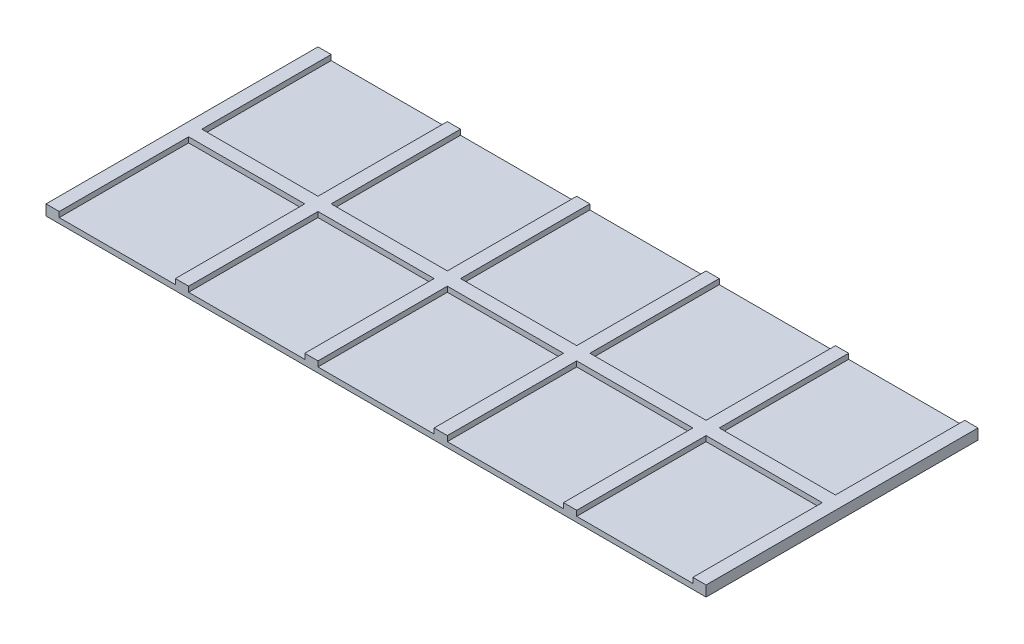
SolidWorks part; units mm, degrees
ref_plane "Front Plane" through (0, 0, 0) normal (0, 0, 1) x (1, 0, 0)
ref_plane "Top Plane" through (0, 0, 0) normal (0, 1, 0) x (1, 0, 0)
ref_plane "Right Plane" through (0, 0, 0) normal (1, 0, 0) x (0, 0, -1)
sketch "Sketch1" plane through (0, 0, 0) normal (0, 1, 0) x (1, 0, 0)
  line L1 (-122.5, 128.75) -> (122.5, 128.75)
  line L5 (122.5, 128.75) -> (367.5, 128.75)
  line L9 (367.5, 128.75) -> (612.5, 128.75)
  line L13 (-367.5, 128.75) -> (-122.5, 128.75)
  line L17 (-612.5, 128.75) -> (-367.5, 128.75)
  line L20 (612.5, 128.75) -> (625, 128.75)
  line L21 (625, 128.75) -> (625, -386.25)
  line L22 (-355, -116.25) -> (-135, -116.25)
  line L23 (-355, -141.25) -> (-135, -141.25)
  line L24 (625, 128.75) -> (600, 128.75)
  line L25 (600, 128.75) -> (600, -386.25)
  line L26 (-110, -116.25) -> (110, -116.25)
  line L27 (355, 128.75) -> (380, 128.75)
  line L28 (380, 128.75) -> (380, -386.25)
  line L30 (355, -386.25) -> (355, 128.75)
  line L31 (110, 128.75) -> (135, 128.75)
  line L32 (135, 128.75) -> (135, -386.25)
  line L34 (110, 128.75) -> (110, -386.25)
  line L35 (625, 128.75) -> (600, 128.75)
  line L36 (-110, -141.25) -> (110, -141.25)
  line L37 (600, 128.75) -> (612.5, 128.75)
  line L38 (-110, 128.75) -> (-135, 128.75)
  line L39 (-135, 128.75) -> (-135, -386.25)
  line L41 (-110, 128.75) -> (-110, -386.25)
  line L43 (-380, 128.75) -> (-380, -386.25)
  line L44 (-355, 128.75) -> (-380, 128.75)
  line L45 (-355, -386.25) -> (-355, 128.75)
  line L46 (135, -116.25) -> (355, -116.25)
  line L47 (-600, 128.75) -> (-600, -386.25)
  line L48 (-625, 128.75) -> (-625, -386.25)
  line L49 (-612.5, 128.75) -> (-625, 128.75)
  line L50 (-600, 128.75) -> (-612.5, 128.75)
  line L52 (-600, -116.25) -> (-380, -116.25)
  line L57 (-600, -386.25) -> (-612.5, -386.25)
  line L58 (-612.5, -386.25) -> (-625, -386.25)
  line L59 (-355, -386.25) -> (-380, -386.25)
  line L60 (-110, -386.25) -> (-135, -386.25)
  line L61 (600, -386.25) -> (612.5, -386.25)
  line L62 (625, -386.25) -> (600, -386.25)
  line L63 (110, -386.25) -> (135, -386.25)
  line L64 (355, -386.25) -> (380, -386.25)
  line L65 (625, -386.25) -> (600, -386.25)
  line L66 (612.5, -386.25) -> (625, -386.25)
  line L67 (-612.5, -386.25) -> (-367.5, -386.25)
  line L68 (-367.5, -386.25) -> (-122.5, -386.25)
  line L69 (367.5, -386.25) -> (612.5, -386.25)
  line L70 (122.5, -386.25) -> (367.5, -386.25)
  line L71 (-122.5, -386.25) -> (122.5, -386.25)
  line L72 (-600, -141.25) -> (-380, -141.25)
  line L73 (135, -141.25) -> (355, -141.25)
  line L74 (380, -116.25) -> (600, -116.25)
  line L75 (380, -141.25) -> (600, -141.25)
  point P0 (0, 0)
  point P25 (0, -128.75)
  point P31 (367.5, 128.75)
  point P35 (122.5, 128.75)
  point P46 (-600, -128.75)
  point P71 (122.5, -386.25)
  point P72 (367.5, -386.25)
  point P73 (0, -257.5)
  point P76 (12.5, -116.25)
  point P79 (12.5, -141.25)
  dimension "D1" = 245
  dimension "D5" = 12.5
  dimension "D6" = 25
  dimension "D7" = 25
  dimension "D8" = 25
extrude "Boss-Extrude1" add sketch "Sketch1" along normal blind 10 contours L58 L57 L47 L17 L49 L48 | L47 L72 L43 L52 | L45 L23 L39 L22 | L60 L41 L1 L13 L39 | L26 L41 L36 L34 | L34 L63 L32 L5 L1 | L32 L73 L30 L46 | L30 L64 L28 L9 L5 | L28 L75 L25 L74 | L62 L21 L20 L9 L25 L61
sketch "Sketch2" plane through (0, 0, 0) normal (0, 1, 0) x (1, 0, 0)
  line L0 (625, -386.25) -> (625, 128.75)
  line L1 (625, -386.25) -> (-625.0619, -386.25)
  line L2 (625, 128.75) -> (-625.0619, 128.75)
  line L3 (-625.0619, -386.25) -> (-625.0619, 128.75)
extrude "Boss-Extrude2" add sketch "Sketch2" against normal blind 10
